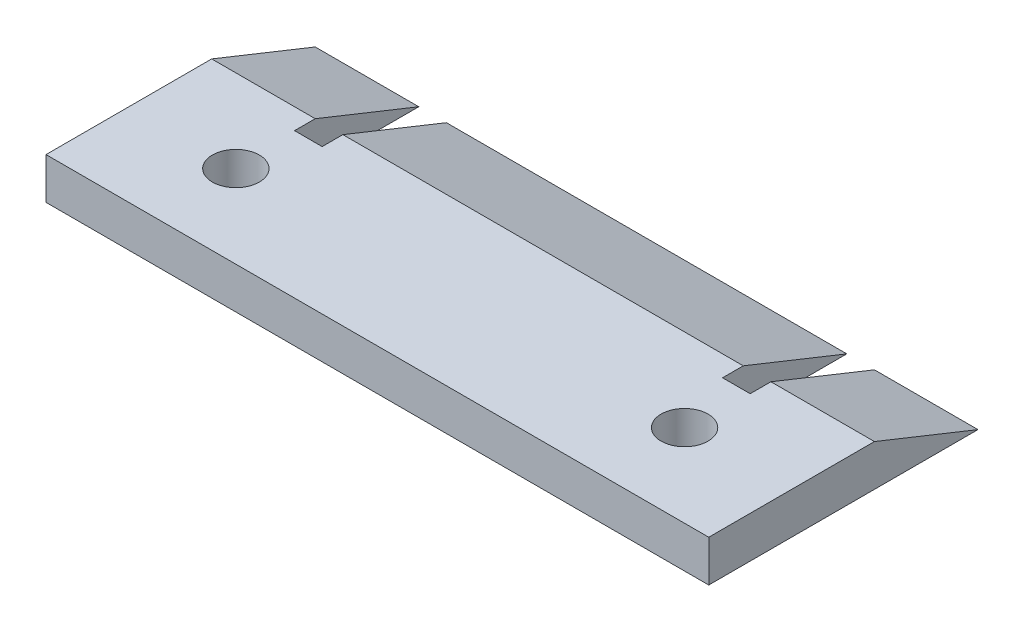
SolidWorks part; units mm, degrees
material "45钢"
ref_plane "前视基准面" through (0, 0, 0) normal (0, 0, 1) x (1, 0, 0)
ref_plane "上视基准面" through (0, 0, 0) normal (0, 1, 0) x (1, 0, 0)
ref_plane "右视基准面" through (0, 0, 0) normal (1, 0, 0) x (0, 0, -1)
sketch "草图1" plane through (0, 0, 0) normal (1, 0, 0) x (0, 0, -1)
  line L0 (39, 0) -> (24, 6)
  line L1 (0, 0) -> (39, 0)
  line L2 (0, 0) -> (0, 6)
  line L3 (0, 6) -> (39, 6)
  line L4 (39, 0) -> (39, 6)
  dimension "D1" = 39
  dimension "D2" = 6
  dimension "D3" = 24
extrude "凸台-拉伸1" add sketch "草图1" along normal mid plane 96 contours L3 L2 L1 L0
sketch "草图2" plane through (0, 6, 0) normal (0, 1, 0) x (1, 0, 0)
  line L0 (-32.5, 12) -> (32.5, 12) construction
  line L2 (0, -3.3) -> (0, 3.3) construction
  line L3 (-3.3, 0) -> (3.3, 0) construction
  point P1 (32.5, 12)
  point P2 (-32.5, 12)
  point P3 (0, 12)
  dimension "D1" = 65
  dimension "D2" = 12
hole_wizard "M8 螺纹孔1" positions "草图2" profile "草图3" tap size "M8" standard "GB"
sketch "草图3" plane through (32.5, 6, -12) normal (1, 0, 0) x (0, 0, 1)
  line L0 (0, 0) -> (0, 6)
  line L1 (0, 6) -> (3.4, 6)
  line L2 (3.4, 6) -> (3.4, 0)
  line L5 (3.4, 0) -> (0, 0)
  line L11 (0, -6.35) -> (0, 107.95) construction
  dimension "通孔螺纹孔钻头直径" = 6.8
  dimension "通孔螺纹孔钻头深度" = 6
cosmetic thread "孔螺纹线1"
cosmetic thread "孔螺纹线2"
sketch "草图4" plane through (0, 6, 0) normal (0, 1, 0) x (1, 0, 0)
  line L0 (-33, 21) -> (-33, 39)
  line L1 (48, 39) -> (-48, 39) construction
  line L2 (48, 0) -> (-48, 0) construction
  dimension "D1" = 21
  dimension "D2" = 33
extrude "切除-拉伸-薄壁1" cut sketch "草图4" against normal through all and the other way through all thin
mirror "镜向1" about plane through (0, 0, 0) normal (1, 0, 0) of "切除-拉伸-薄壁1"
